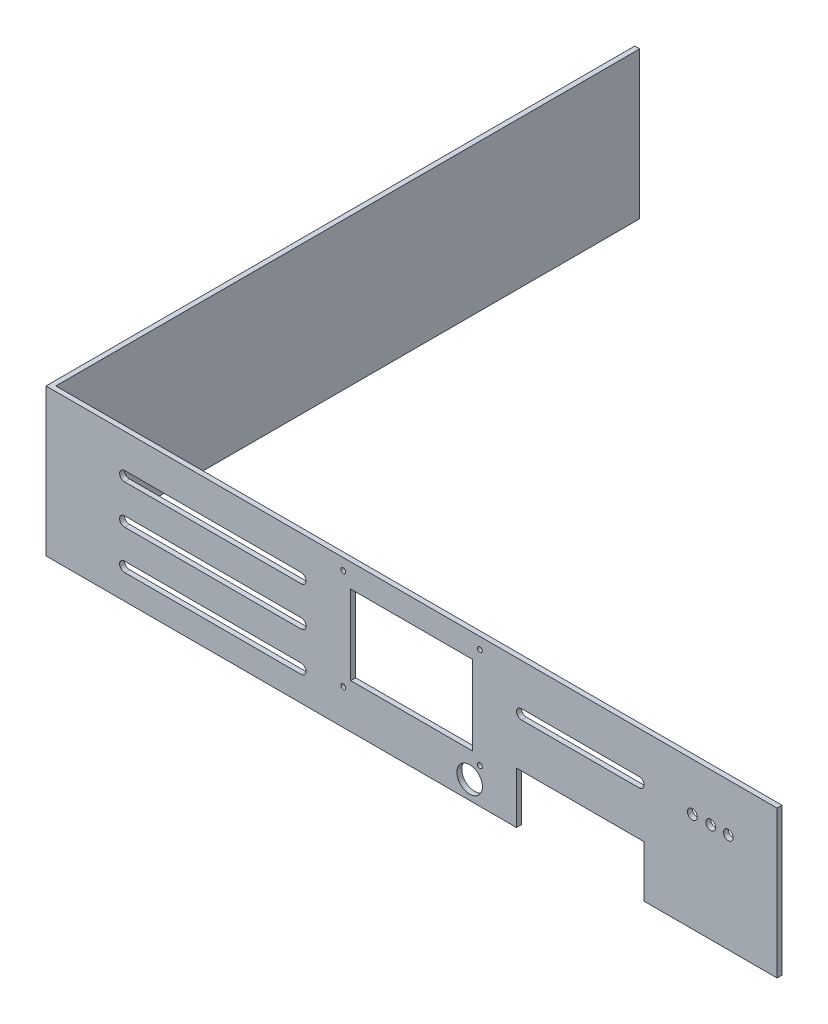
SolidWorks part; units mm, degrees
ref_plane "Front Plane" through (0, 0, 0) normal (0, 0, 1) x (1, 0, 0)
ref_plane "Top Plane" through (0, 0, 0) normal (0, 1, 0) x (1, 0, 0)
ref_plane "Right Plane" through (0, 0, 0) normal (1, 0, 0) x (0, 0, -1)
sketch "Sketch1" plane through (0, 0, 0) normal (0, 0, 1) x (1, 0, 0)
  line L1 (-236.5375, -47.625) -> (236.5375, -47.625)
  line L2 (-236.5375, -47.625) -> (-236.5375, 47.625)
  line L3 (-236.5375, 47.625) -> (236.5375, 47.625)
  line L4 (236.5375, -47.625) -> (236.5375, 47.625)
  line L5 (-236.5375, -47.625) -> (236.5375, 47.625) construction
  line L6 (-236.5375, 47.625) -> (236.5375, -47.625) construction
  point P0 (0, 0)
  dimension "D1" = 473.075
  dimension "D2" = 95.25
extrude "Boss-Extrude1" add sketch "Sketch1" along normal blind 3.175
sketch "Sketch3" plane through (0, 0, 3.175) normal (0, 0, 1) x (1, 0, 0)
  line L0 (0, -47.625) -> (0, -19.05)
  line L1 (-236.5375, -47.625) -> (236.5375, -47.625) construction
  line L3 (-39.37, -18.923) -> (39.37, -18.923)
  line L4 (-39.37, -18.923) -> (-39.37, 32.385)
  line L5 (-39.37, 32.385) -> (39.37, 32.385)
  line L6 (39.37, -18.923) -> (39.37, 32.385)
  dimension "D1" = 28.575
  dimension "D2" = 78.74
  dimension "D3" = 39.37
  dimension "D4" = 51.308
  dimension "D5" = 28.702
extrude "Cut-Extrude2" cut sketch "Sketch3" against normal through all contours L3 L6 L5 L4
sketch "Sketch4" plane through (0, 0, 3.175) normal (0, 0, 1) x (1, 0, 0)
  line L0 (-236.5375, -47.625) -> (236.5375, -47.625) construction
  line L1 (39.37, -18.923) -> (39.37, 32.385) construction
  circle A0 centre (37.592, -35.814) radius 8.255
  dimension "D1" = 16.51
  dimension "D2" = 11.811
  dimension "D3" = 1.778
extrude "Cut-Extrude3" cut sketch "Sketch4" against normal through all
sketch "Sketch5" plane through (0, 0, 3.175) normal (0, 0, 1) x (1, 0, 0)
  line L0 (39.37, -18.923) -> (39.37, 32.385) construction
  line L1 (-39.37, 32.385) -> (39.37, 32.385) construction
  line L2 (0, 0) -> (0, 11.1381)
  line L3 (0, 0) -> (6.9433, 0)
  circle A0 centre (44.196, 40.259) radius 1.5875
  circle A1 centre (44.196, -24.765) radius 1.5875
  circle A2 centre (-44.196, -24.765) radius 1.5875
  circle A3 centre (-44.196, 40.259) radius 1.5875
  dimension "D1" = 3.175
  dimension "D3" = 7.874
  dimension "D4" = 65.024
  dimension "D5" = 0
  dimension "D2" = 4.826
extrude "Cut-Extrude4" cut sketch "Sketch5" against normal through all contours A3 | A0 | A2 | A1
sketch "Sketch6" plane through (0, 0, 0) normal (0, 0, -1) x (-1, 0, 0)
  line L0 (236.5375, -47.625) -> (-236.5375, -47.625) construction
  line L1 (236.5375, 47.625) -> (233.3625, 47.625)
  line L2 (236.5375, 47.625) -> (236.5375, -47.625)
  line L3 (236.5375, -47.625) -> (233.3625, -47.625)
  line L4 (233.3625, 47.625) -> (233.3625, -47.625)
  dimension "D1" = 3.175
extrude "Boss-Extrude2" add sketch "Sketch6" along normal blind 377.825
sketch "Sketch7" plane through (-236.5375, 0, 0) normal (-1, 0, 0) x (0, 0, 1)
  line L0 (3.175, 47.625) -> (-377.825, 47.625) construction
  line L1 (-339.725, 28.575) -> (-288.925, 28.575)
  line L2 (-339.725, 28.575) -> (-339.725, -44.45)
  line L3 (-339.725, -44.45) -> (-288.925, -44.45)
  line L4 (-288.925, 28.575) -> (-288.925, -44.45)
  line L5 (-377.825, -47.625) -> (-377.825, 47.625) construction
  line L6 (3.175, -47.625) -> (-377.825, -47.625) construction
  circle A0 centre (-254.127, -28.575) radius 3.81
  dimension "D5" = 123.698
  dimension "D6" = 19.05
  dimension "D1" = 19.05
  dimension "D2" = 50.8
  dimension "D3" = 38.1
  dimension "D4" = 3.175
sketch "Sketch8" plane through (0, 0, 3.175) normal (0, 0, 1) x (1, 0, 0)
  line L0 (-236.5375, -47.625) -> (-185.7375, -47.625)
  line L1 (-236.5375, -47.625) -> (236.5375, -47.625) construction
  line L5 (-185.7375, -28.3064) -> (-71.4375, -28.3064) construction
  line L6 (-185.7375, -25.1314) -> (-71.4375, -25.1314)
  line L7 (-185.7375, -31.4814) -> (-71.4375, -31.4814)
  line L8 (-185.7375, -2.9064) -> (-71.4375, -2.9064) construction
  line L9 (-185.7375, 0.2686) -> (-71.4375, 0.2686)
  line L10 (-185.7375, -6.0814) -> (-71.4375, -6.0814)
  line L11 (-185.7375, 22.4936) -> (-71.4375, 22.4936) construction
  line L12 (-185.7375, 25.6686) -> (-71.4375, 25.6686)
  line L13 (-185.7375, 19.3186) -> (-71.4375, 19.3186)
  line L15 (71.12, 17.4499) -> (147.32, 17.4499) construction
  line L16 (71.12, 20.6249) -> (147.32, 20.6249)
  line L17 (71.12, 14.2749) -> (147.32, 14.2749)
  line L20 (67.945, -14.3001) -> (150.495, -14.3001)
  line L21 (67.945, -14.3001) -> (67.945, -47.625)
  line L22 (67.945, -47.625) -> (150.495, -47.625)
  line L23 (150.495, -14.3001) -> (150.495, -47.625)
  arc A0 (-185.7375, -25.1314) -> (-185.7375, -31.4814) centre (-185.7375, -28.3064) ccw
  arc A1 (-71.4375, -31.4814) -> (-71.4375, -25.1314) centre (-71.4375, -28.3064) ccw
  arc A2 (-185.7375, 0.2686) -> (-185.7375, -6.0814) centre (-185.7375, -2.9064) ccw
  arc A3 (-71.4375, -6.0814) -> (-71.4375, 0.2686) centre (-71.4375, -2.9064) ccw
  arc A4 (-185.7375, 25.6686) -> (-185.7375, 19.3186) centre (-185.7375, 22.4936) ccw
  arc A5 (-71.4375, 19.3186) -> (-71.4375, 25.6686) centre (-71.4375, 22.4936) ccw
  arc A6 (71.12, 20.6249) -> (71.12, 14.2749) centre (71.12, 17.4499) ccw
  arc A7 (147.32, 14.2749) -> (147.32, 20.6249) centre (147.32, 17.4499) ccw
  point P5 (-128.5875, -28.3064)
  point P14 (-128.5875, -2.9064)
  point P20 (-128.5875, 22.4936)
  point P31 (109.22, 17.4499)
  line M17 (-236.5375, -47.625) -> (236.5375, -47.625)
extrude "Cut-Extrude6" cut sketch "Sketch8" against normal blind 29.464 contours L23 L20 L21 M17 | L17 A7 L16 A6 | L13 A5 L12 A4 | L10 A3 L9 A2 | L7 A1 L6 A0
sketch "Sketch9" plane through (0, 0, 3.175) normal (0, 0, 1) x (1, 0, 0)
  circle A0 centre (181.7157, 16.7257) radius 3.175
  circle A1 centre (193.5994, 16.7257) radius 3.175
  circle A3 centre (204.9103, 16.7257) radius 3.175
  point P8 (193.3304, 17.8015)
  point P9 (193.5994, 16.7257)
  point P10 (204.9103, 16.7257)
extrude "Cut-Extrude7" cut sketch "Sketch9" against normal through all
